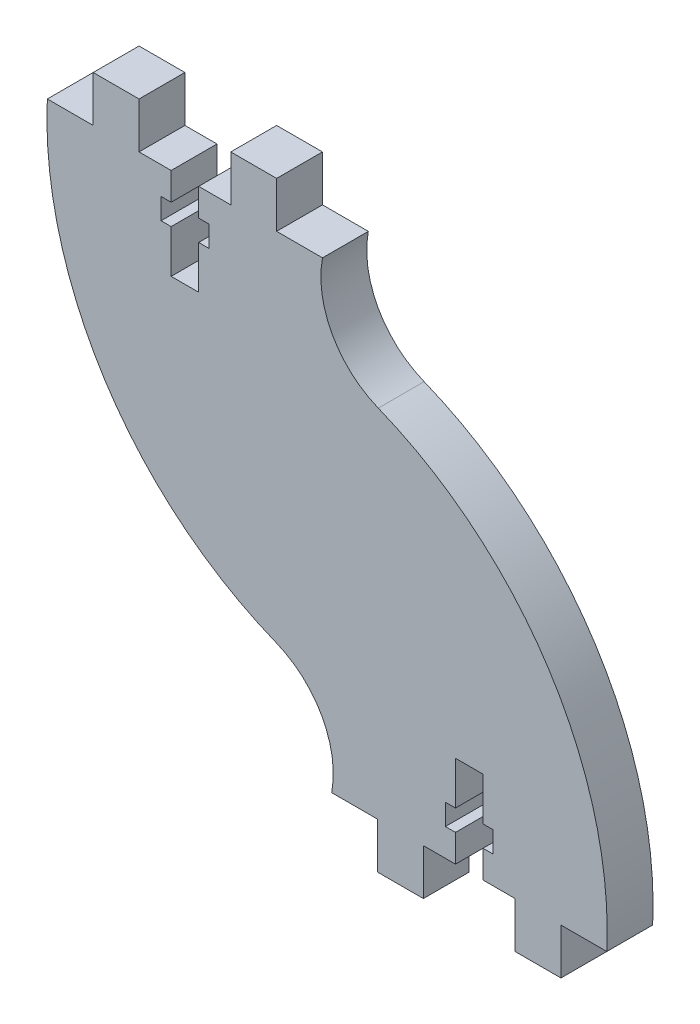
SolidWorks part; units mm, degrees
ref_plane "Front Plane" through (0, 0, 0) normal (0, 0, 1) x (1, 0, 0)
ref_plane "Top Plane" through (0, 0, 0) normal (0, 1, 0) x (1, 0, 0)
ref_plane "Right Plane" through (0, 0, 0) normal (1, 0, 0) x (0, 0, -1)
sketch "Sketch1" plane through (0, 0, 0) normal (0, 0, 1) x (1, 0, 0)
  line L1 (-5, 0) -> (25, 0) construction
  line L8 (0.0836, 38.8502) -> (-11.0836, 11.1498) construction
  line L17 (-5, 0) -> (-6, 50) construction
  line L29 (-11, 50) -> (-6, 50)
  line L30 (-31, 50) -> (-36, 50)
  line L39 (-5, 0) -> (0, 0)
  line L51 (20, 0) -> (25, 0)
  line L52 (-36, 50) -> (-5, 0) construction
  line L53 (25, 0) -> (-6, 50) construction
  arc A0 (-6, 50) -> (0.0836, 38.8502) centre (3.8226, 48.1249) ccw
  arc A1 (0.0836, 38.8502) -> (25, 0) centre (-14.8226, 1.8751) cw
  arc A2 (-36, 50) -> (-11.0836, 11.1498) centre (3.8226, 48.1249) ccw
  arc A3 (-11.0836, 11.1498) -> (-5, 0) centre (-14.8226, 1.8751) cw
  point P2 (-5.5, 25)
  point P7 (-5.5, 25)
  point P20 (10, 0)
  line B0 (-18.4, 47) -> (-18.4, 44.7)
  line B1 (-22.5, 44.7) -> (-22.5, 40)
  line B2 (-19.5, 40) -> (-19.5, 44.7)
  line B3 (-18.4, 44.7) -> (-19.5, 44.7)
  line B4 (-21, 50) -> (-21, 38.7792) construction
  line B5 (-19.5, 50) -> (-16, 50)
  line B6 (-16, 55) -> (-11, 55)
  line B7 (-11, 55) -> (-11, 50)
  line B8 (-16, 55) -> (-16, 50)
  line B9 (-22.5, 50) -> (-26, 50)
  line B10 (-26, 50) -> (-26, 55)
  line B11 (-26, 55) -> (-31, 55)
  line B12 (-31, 55) -> (-31, 50)
  line B13 (-19.5, 50) -> (-22.5, 50) construction
  line B14 (-22.5, 50) -> (-22.5, 47)
  line B15 (-22.5, 44.7) -> (-23.6, 44.7)
  line B16 (-23.6, 47) -> (-22.5, 47)
  line B17 (-22.5, 40) -> (-19.5, 40)
  line B18 (-19.5, 47) -> (-18.4, 47)
  line B19 (-23.6, 44.7) -> (-23.6, 47)
  line B20 (-19.5, 47) -> (-19.5, 50)
  line B21 (-21, 40) -> (-21, 50) construction
  line B22 (7.4, 3) -> (7.4, 5.3)
  line B23 (11.5, 5.3) -> (11.5, 10)
  line B24 (8.5, 10) -> (8.5, 5.3)
  line B25 (7.4, 5.3) -> (8.5, 5.3)
  line B26 (10, 0) -> (10, 11.2208) construction
  line B27 (8.5, 0) -> (5, 0)
  line B28 (5, -5) -> (0, -5)
  line B29 (0, -5) -> (0, 0)
  line B30 (5, -5) -> (5, 0)
  line B31 (11.5, 0) -> (15, 0)
  line B32 (15, 0) -> (15, -5)
  line B33 (15, -5) -> (20, -5)
  line B34 (20, -5) -> (20, 0)
  line B35 (8.5, 0) -> (11.5, 0) construction
  line B36 (11.5, 0) -> (11.5, 3)
  line B37 (11.5, 5.3) -> (12.6, 5.3)
  line B38 (12.6, 3) -> (11.5, 3)
  line B39 (11.5, 10) -> (8.5, 10)
  line B40 (8.5, 3) -> (7.4, 3)
  line B41 (12.6, 5.3) -> (12.6, 3)
  line B42 (8.5, 3) -> (8.5, 0)
  line B43 (10, 10) -> (10, 0) construction
  dimension "D3" = 10
  dimension "D1" = 50
  dimension "D2" = 31
  dimension "D4" = 5
sketch_block_instance "Insert M3 plots ep 5mm-1"
sketch_block "Insert M3 plots ep 5mm" parameters "D1"=10, "D2"=5, "D3"=5
sketch_block_instance "Decoupe Insert M3-4"
sketch_block "Decoupe Insert M3" parameters "D1"=5.2, "D2"=3, "D3"=2.3, "D4"=3, "D5"=10
sketch_block_instance "Insert M3 plots ep 5mm-3"
extrude "Boss-Extrude1" add sketch "Sketch1" along normal blind 5 contours B42 B40 B22 B25 B24 B39 B23 B37 B41 B38 B36 B31 B32 B33 B34 A1 A0 B7 B6 B8 B5 B20 B18 B0 B3 B2 B17 B1 B15 B19 B16 B14 B9 B10 B11 B12 A2 A3 B29 B28 B30 B27
